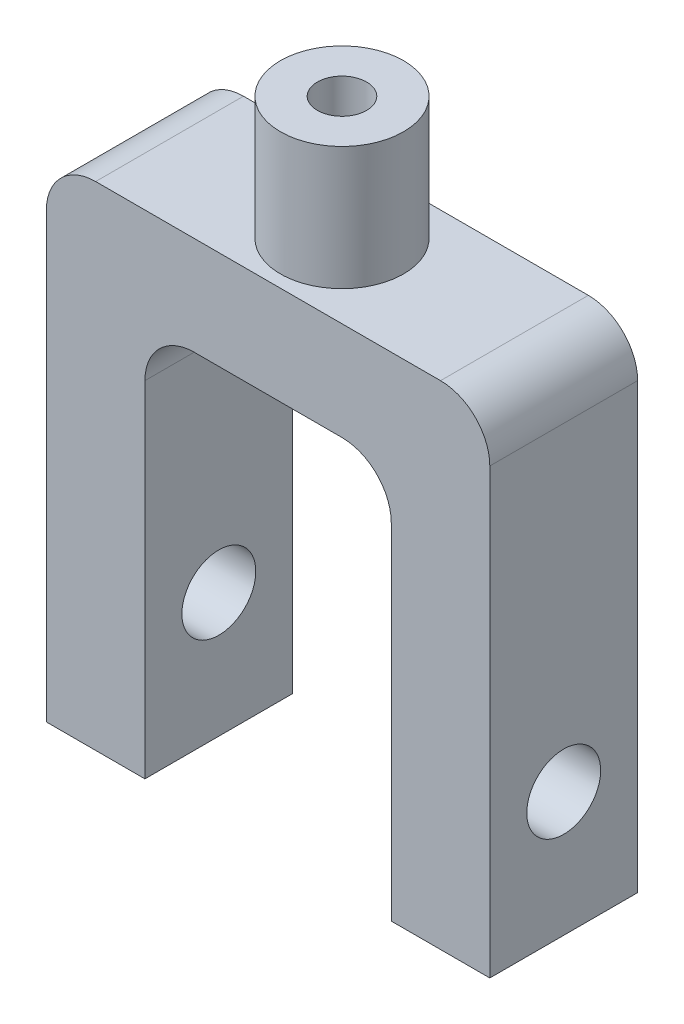
SolidWorks part; units mm, degrees
ref_plane "Front Plane" through (0, 0, 0) normal (0, 0, 1) x (1, 0, 0)
ref_plane "Top Plane" through (0, 0, 0) normal (0, 1, 0) x (1, 0, 0)
ref_plane "Right Plane" through (0, 0, 0) normal (1, 0, 0) x (0, 0, -1)
sketch "Sketch1" plane through (0, 0, 0) normal (0, 0, 1) x (1, 0, 0)
  line L0 (0, 0) -> (0, 100)
  line L1 (0, 100) -> (90, 100)
  line L2 (90, 100) -> (90, 0)
  line L3 (0, 0) -> (20, 0)
  line L4 (20, 0) -> (20, 80)
  line L5 (20, 80) -> (70, 80)
  line L6 (70, 80) -> (70, 0)
  line L7 (70, 0) -> (90, 0)
  dimension "D1" = 20
  dimension "D2" = 20
  dimension "D3" = 20
  dimension "D4" = 100
  dimension "D5" = 50
extrude "Boss-Extrude1" add sketch "Sketch1" along normal blind 30
fillet "Fillet1" radius 10 4 edges at (70, 80, 15) (20, 80, 15) (0, 100, 15) (90, 100, 15)
sketch "Sketch2" plane through (90, 0, 0) normal (1, 0, 0) x (0, 0, -1)
  line L0 (0, 0) -> (0, 90) construction
  circle A0 centre (-15, 25.2499) radius 7.5
  dimension "D2" = 15
  dimension "D1" = 15
extrude "Cut-Extrude1" cut sketch "Sketch2" against normal through all
sketch "Sketch3" plane through (0, 100, 0) normal (0, 1, 0) x (1, 0, 0)
  line L0 (80, 0) -> (10, 0) construction
  line L1 (0, -30) -> (0, 0) construction
  circle A0 centre (45, -15) radius 12.5
  circle A1 centre (45, -15) radius 5
  dimension "D2" = 25
  dimension "D3" = 10
  dimension "D1" = 15
  dimension "D4" = 45
extrude "Boss-Extrude2" add sketch "Sketch3" along normal blind 25
